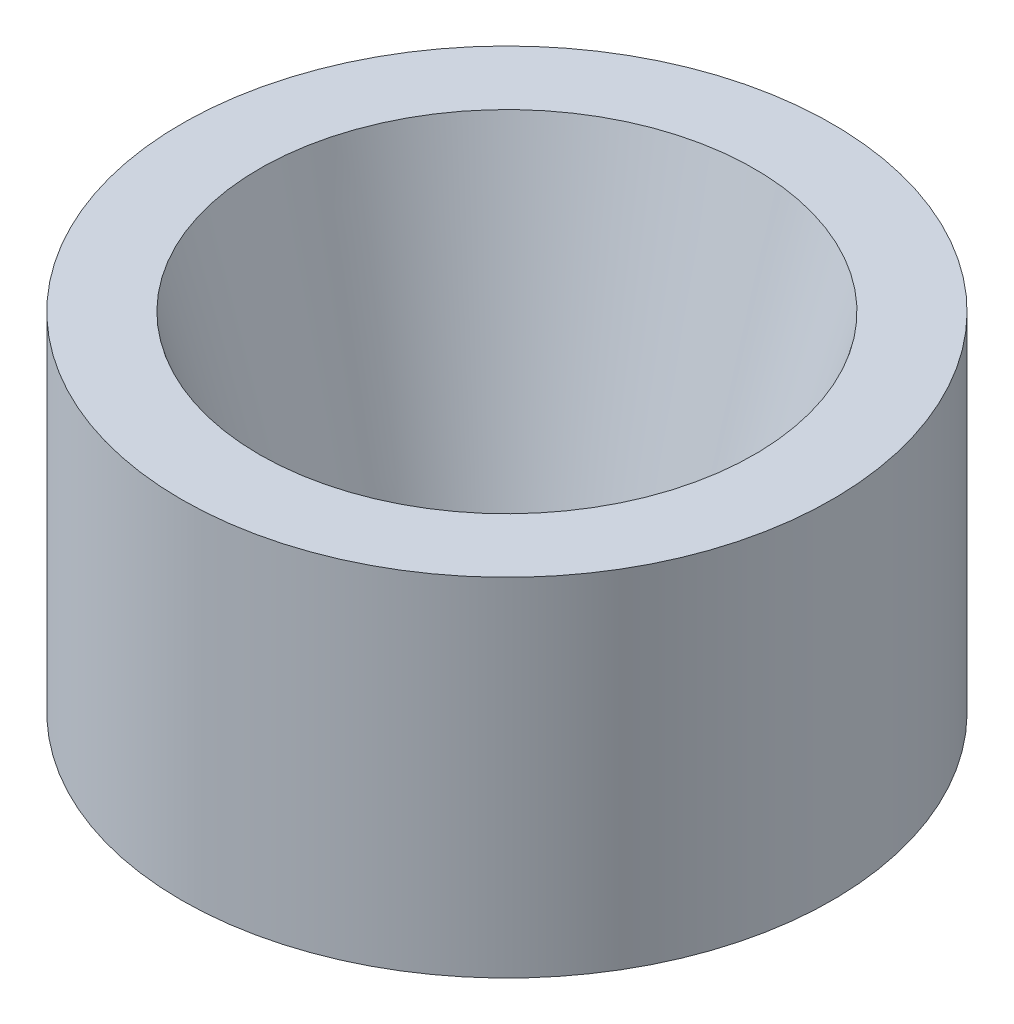
SolidWorks part; units mm, degrees
ref_plane "Plan de face" through (0, 0, 0) normal (0, 0, 1) x (1, 0, 0)
ref_plane "Plan de dessus" through (0, 0, 0) normal (0, 1, 0) x (1, 0, 0)
ref_plane "Plan de droite" through (0, 0, 0) normal (1, 0, 0) x (0, 0, -1)
sketch "Esquisse1" plane through (0, 0, 0) normal (0, 0, 1) x (1, 0, 0)
  line L0 (-5.7057, 0) -> (-3.8027, -7.1021)
  line L1 (-3.8027, -7.1021) -> (-3.8027, -8)
  line L2 (-3.8027, -8) -> (-7.5, -8)
  line L3 (-7.5, -8) -> (-7.5, 0)
  line L4 (-7.5, 0) -> (-5.7057, 0)
  line L5 (0, 0) -> (0, -28.9939) construction
  dimension "D1" = 15
  dimension "D2" = 8
  dimension "D3" = 15
revolve "Révolution1" add sketch "Esquisse1" angle 360 about L5
